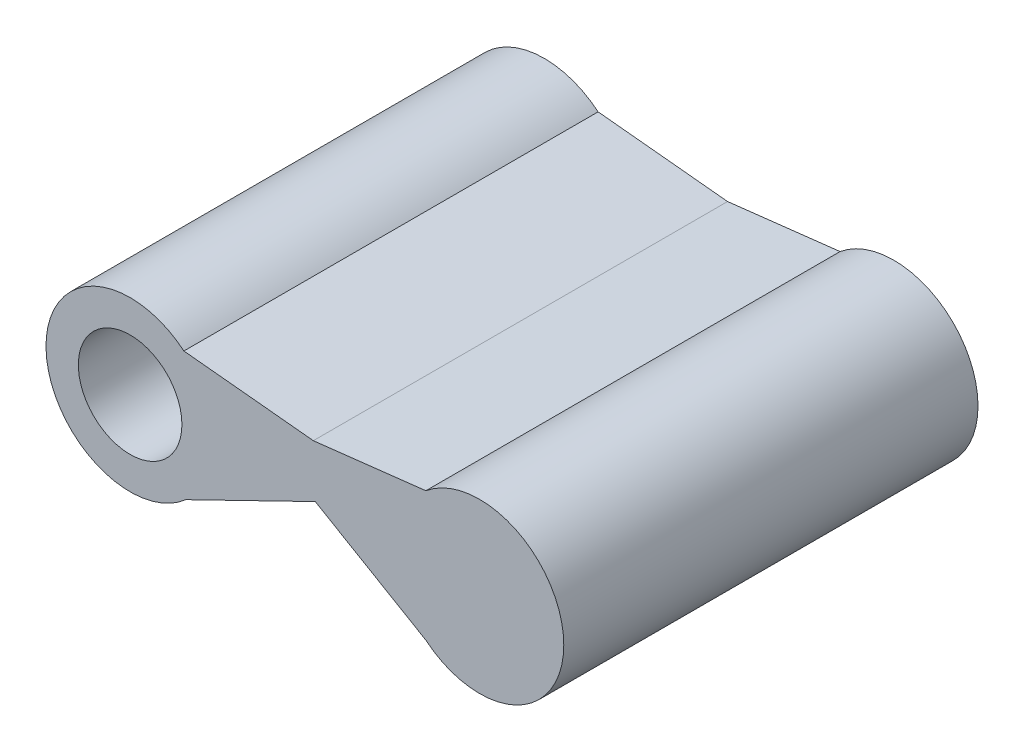
SolidWorks part; units mm, degrees
ref_plane "Front Plane" through (0, 0, 0) normal (0, 0, 1) x (1, 0, 0)
ref_plane "Top Plane" through (0, 0, 0) normal (0, 1, 0) x (1, 0, 0)
ref_plane "Right Plane" through (0, 0, 0) normal (1, 0, 0) x (0, 0, -1)
sketch "Sketch1" plane through (0, 0, 0) normal (0, 0, 1) x (1, 0, 0)
  line L0 (2.0767, 2.5) -> (7.0767, 2)
  line L1 (1.5608, 2.5) -> (12.7425, 2.5) construction
  line L2 (1.5608, 2.5) -> (1.5608, -2.5) construction
  line L3 (1.5608, -2.5) -> (12.7425, -2.5) construction
  line L4 (12.7425, 2.5) -> (12.7425, -2.5) construction
  line L5 (1.5608, 2.5) -> (12.7425, -2.5) construction
  line L6 (1.5608, -2.5) -> (12.7425, 2.5) construction
  line L7 (7.0767, 2) -> (11.4233, 2.5)
  line L8 (2.1516, -2.4358) -> (7.1516, 0)
  line L9 (7.1516, 0) -> (11.4233, -2.5)
  arc A0 (2.0767, 2.5) -> (2.1516, -2.4358) centre (0, 0) ccw
  circle A1 centre (0, 0) radius 2
  arc A2 (11.4233, -2.5) -> (11.4233, 2.5) centre (13.5, 0) ccw
  point P10 (7.1516, 0)
  dimension "D1" = 4
  dimension "D2" = 6.5
  dimension "D3" = 13.5
  dimension "D4" = 5
  dimension "D5" = 2.5
  dimension "D6" = 1
  dimension "D7" = 5
  dimension "D8" = 5
  dimension "D9" = 2.4358
extrude "Boss-Extrude1" add sketch "Sketch1" along normal blind 16
ref_plane "Plane1" through (0, 0, 8) normal (0, 0, -1) x (-1, 0, 0)
